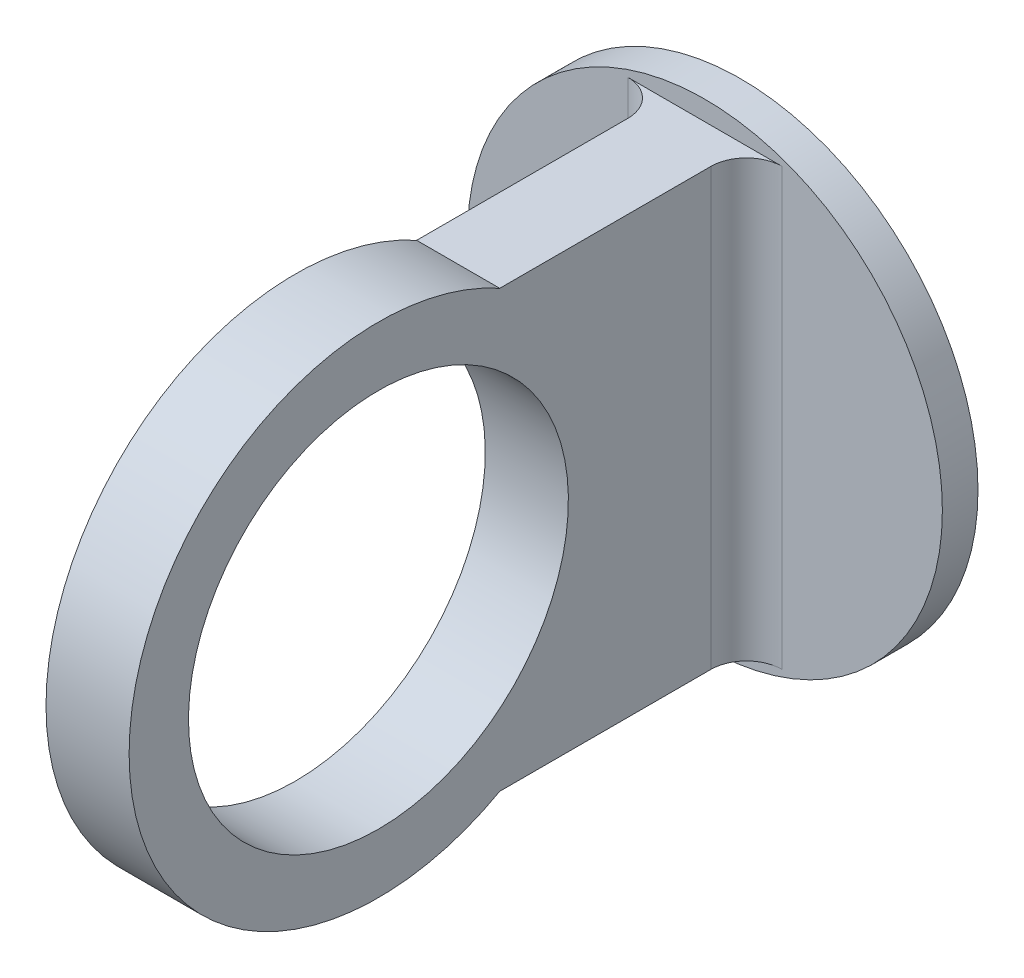
SolidWorks part; units mm, degrees
ref_plane "Front Plane" through (0, 0, 0) normal (0, 0, 1) x (1, 0, 0)
ref_plane "Top Plane" through (0, 0, 0) normal (0, 1, 0) x (1, 0, 0)
ref_plane "Right Plane" through (0, 0, 0) normal (1, 0, 0) x (0, 0, -1)
sketch "Sketch1" plane through (0, 0, 0) normal (0, 0, 1) x (1, 0, 0)
  circle A0 centre (0, 0) radius 20
  dimension "D1" = 40
extrude "Boss-Extrude1" add sketch "Sketch1" along normal blind 3
sketch "Sketch2" plane through (0, 0, 0) normal (0, 0, -1) x (-1, 0, 0)
  line L1 (-3.5, 18.3466) -> (3.5, 18.3466)
  line L2 (-3.5, 18.3466) -> (-3.5, -18.3466)
  line L3 (-3.5, -18.3466) -> (3.5, -18.3466)
  line L4 (3.5, 18.3466) -> (3.5, -18.3466)
  line L5 (-3.5, 18.3466) -> (3.5, -18.3466) construction
  line L6 (-3.5, -18.3466) -> (3.5, 18.3466) construction
  point P0 (0, 0)
  dimension "D1" = 7
extrude "Boss-Extrude2" add sketch "Sketch2" against normal blind 30
fillet "Fillet2" radius 3 2 edges at (-3.5, 0, 3) (3.5, 0, 3)
sketch "Sketch3" plane through (-3.5, 0, 0) normal (-1, 0, 0) x (0, 0, 1)
  line L0 (6, 18.3466) -> (6, -18.3466) construction
  circle A0 centre (34, 0) radius 21
  circle A1 centre (34, 0) radius 16
  dimension "D1" = 42
  dimension "D2" = 32
  dimension "D3" = 28
extrude "Boss-Extrude3" add sketch "Sketch3" against normal blind 7
sketch "Sketch4" plane through (-3.5, 0, 0) normal (-1, 0, 0) x (0, 0, 1)
  circle A0 centre (34, 0) radius 16
extrude "Cut-Extrude1" cut sketch "Sketch4" against normal blind 7
